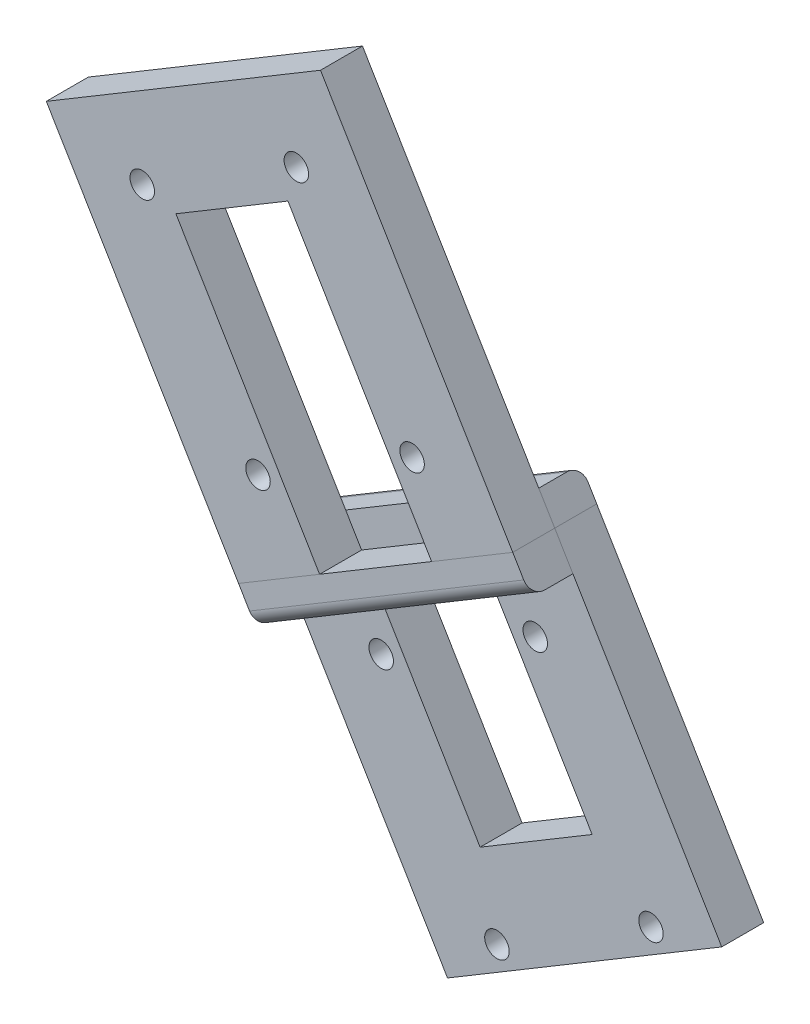
SolidWorks part; units mm, degrees
ref_plane "前视基准面" through (0, 0, 0) normal (0, 0, 1) x (1, 0, 0)
ref_plane "上视基准面" through (0, 0, 0) normal (0, 1, 0) x (1, 0, 0)
ref_plane "右视基准面" through (0, 0, 0) normal (1, 0, 0) x (0, 0, -1)
other "Configuration Table"
sketch "草图2" plane through (0, 0, 0) normal (0, 0, 1) x (1, 0, 0)
  line L2 (-562.0337, 913.0338) -> (-46.9087, 51.8379) construction
  line L5 (-22.0945, -34.1131) -> (-73.4273, 51.7061)
  line L6 (-34.2499, 75.1409) -> (-73.4273, 51.7061)
  line L7 (-34.2499, 75.1409) -> (17.083, -10.6784)
  line L8 (17.083, -10.6784) -> (-22.0945, -34.1131)
  line L9 (-6.7787, 29.214) -> (-18.3643, 22.284)
  line L14 (-6.7787, 29.214) -> (-18.3643, 22.284) construction
  line L15 (-34.2499, 75.1409) -> (17.083, -10.6784)
  line L16 (17.083, -10.6784) -> (-22.0945, -34.1131)
  line L17 (-22.0945, -34.1131) -> (-73.4273, 51.7061)
  line L18 (-34.2499, 75.1409) -> (-73.4273, 51.7061)
  line L19 (-38.9054, 56.6252) -> (-1.4325, -6.0229)
  line L20 (-1.4325, -6.0229) -> (-17.4389, -15.5974)
  line L21 (-17.4389, -15.5974) -> (-54.9119, 47.0506)
  line L22 (-38.9054, 56.6252) -> (-54.9119, 47.0506)
  line L23 (-9.4357, -10.8101) -> (526.6252, -907.007) construction
  line L24 (-34.3708, 12.7097) -> (-45.9564, 5.7798)
  line L25 (-34.3708, 12.7097) -> (-45.9564, 5.7798) construction
  circle A0 centre (-43.1752, 20.6108) radius 1.75 construction
  circle A1 centre (-21.1611, 33.7781) radius 1.75 construction
  circle A2 centre (-59.7122, 48.2576) radius 1.75 construction
  circle A3 centre (-37.6984, 61.4255) radius 1.75 construction
  circle A4 centre (-43.1752, 20.6108) radius 1.75
  circle A5 centre (-21.1611, 33.7781) radius 1.75
  circle A6 centre (-59.7122, 48.2576) radius 1.75
  circle A7 centre (-37.6984, 61.4255) radius 1.75
  circle A8 centre (6.9773, -13.2642) radius 1.75
  circle A9 centre (-15.0368, -26.4315) radius 1.75
  circle A10 centre (-31.5738, 1.2153) radius 1.75
  circle A11 centre (-9.56, 14.3832) radius 1.75
  point P36 (0, 0)
  circle M17 centre (-37.6984, 61.4255) radius 1.75
  circle M18 centre (-59.7122, 48.2576) radius 1.75
  circle M19 centre (-43.1752, 20.6108) radius 1.75
  circle M24 centre (-21.1611, 33.7781) radius 1.75
  arc M29 (-26.0215, 33.3432) -> (-24.3219, 32.2889) centre (-24.2586, 34.2879) ccw
  arc M30 (-24.3219, 32.2889) -> (-23.0277, 31.7586) centre (-24.3852, 30.2899) cw
  arc M31 (-23.0277, 31.7586) -> (-19.5648, 36.0174) centre (-21.1611, 33.7781) ccw
  arc M32 (-19.5648, 36.0174) -> (-20.1027, 38.7014) centre (-18.4039, 37.646) cw
  arc M33 (-20.1027, 38.7014) -> (-15.0628, 52.7838) centre (-50.2567, 57.4361) ccw
  arc M61 (-62.7646, 24.2125) -> (-48.0136, 22.007) centre (-50.2567, 57.4361) ccw
  arc M62 (-48.0136, 22.007) -> (-45.9032, 20.2635) centre (-47.8872, 20.011) cw
  arc M63 (-45.9032, 20.2635) -> (-40.513, 21.3001) centre (-43.1752, 20.6108) ccw
  arc M64 (-40.513, 21.3001) -> (-40.368, 22.6912) centre (-38.5769, 21.8014) cw
  arc M65 (-40.368, 22.6912) -> (-40.493, 24.6873) centre (-42.1592, 23.581) ccw
  dimension "D1" = 13.5
extrude "凸台-拉伸1" add sketch "草图2" along normal blind 6 contours L22 L19 L7 L6 L5 L21 M29 M30 M31 M32 M33 M61 M62 M63 M64 M65 M18 M24 M19 M17 | L19 L9 L7 M29 M33 M32 M31 M30 | L24 L21 L17 M65 M64 M63 M62 M61
sketch "草图3" plane through (0, 0, 0) normal (0, 0, -1) x (-1, 0, 0)
  line L0 (34.3708, 12.7097) -> (45.9564, 5.7798) construction
  line L1 (6.7787, 29.214) -> (18.3643, 22.284) construction
  line L2 (34.3708, 12.7097) -> (45.9564, 5.7798)
  line L3 (6.7787, 29.214) -> (18.3643, 22.284)
  line L4 (38.9054, 56.6252) -> (1.4325, -6.0229)
  line L5 (1.4325, -6.0229) -> (17.4389, -15.5974)
  line L6 (17.4389, -15.5974) -> (54.9119, 47.0506)
  line L7 (54.9119, 47.0506) -> (38.9054, 56.6252)
  line L8 (38.9054, 56.6252) -> (1.4325, -6.0229)
  line L9 (1.4325, -6.0229) -> (17.4389, -15.5974)
  line L10 (17.4389, -15.5974) -> (54.9119, 47.0506)
  line L11 (54.9119, 47.0506) -> (38.9054, 56.6252)
  line L12 (34.2499, 75.1409) -> (-17.083, -10.6784)
  line L13 (-17.083, -10.6784) -> (22.0945, -34.1131)
  line L14 (22.0945, -34.1131) -> (73.4273, 51.7061)
  line L15 (73.4273, 51.7061) -> (34.2499, 75.1409)
  line L16 (34.2499, 75.1409) -> (-17.083, -10.6784)
  line L17 (-17.083, -10.6784) -> (22.0945, -34.1131)
  line L18 (22.0945, -34.1131) -> (73.4273, 51.7061)
  line L19 (73.4273, 51.7061) -> (34.2499, 75.1409)
  line L20 (34.2499, 75.1409) -> (-17.083, -10.6784)
  line L21 (-17.083, -10.6784) -> (22.0945, -34.1131)
  line L22 (22.0945, -34.1131) -> (73.4273, 51.7061)
  line L23 (73.4273, 51.7061) -> (34.2499, 75.1409)
  line L24 (34.2499, 75.1409) -> (-17.083, -10.6784)
  line L25 (-17.083, -10.6784) -> (22.0945, -34.1131)
  line L26 (22.0945, -34.1131) -> (73.4273, 51.7061)
  line L27 (73.4273, 51.7061) -> (34.2499, 75.1409)
  circle A1 centre (37.6984, 61.4255) radius 1.75
  circle A2 centre (37.6984, 61.4255) radius 1.75
  circle A3 centre (59.7122, 48.2576) radius 1.75
  circle A4 centre (59.7122, 48.2576) radius 1.75
  circle A5 centre (21.1611, 33.7781) radius 1.75
  circle A6 centre (21.1611, 33.7781) radius 1.75
  circle A7 centre (43.1752, 20.6108) radius 1.75
  circle A8 centre (43.1752, 20.6108) radius 1.75
  circle A9 centre (9.56, 14.3832) radius 1.75
  circle A10 centre (9.56, 14.3832) radius 1.75
  circle A11 centre (31.5738, 1.2153) radius 1.75
  circle A12 centre (31.5738, 1.2153) radius 1.75
  circle A13 centre (15.0368, -26.4315) radius 1.75
  circle A14 centre (15.0368, -26.4315) radius 1.75
  circle A15 centre (-6.9773, -13.2642) radius 1.75
  circle A16 centre (-6.9773, -13.2642) radius 1.75
  line M23 (34.3708, 12.7097) -> (45.9564, 5.7798)
  line M27 (6.7787, 29.214) -> (18.3643, 22.284)
  dimension "D1" = 0
  dimension "D2" = 0
  dimension "D3" = 0
  dimension "D4" = 0
  dimension "D5" = 0
  dimension "D6" = 0
  dimension "D7" = 0
  dimension "D8" = 0
  dimension "D9" = 0
  dimension "D10" = 0
  dimension "D11" = 0
extrude "凸台-拉伸2" add sketch "草图3" along normal blind 6 separate body contours L17 L18 L10 L9 L8 L16 A16 A14 A12 A10 M23 M27
sketch "草图4" plane through (7.8773, 4.7118, 0) normal (0.8582, 0.5133, 0) x (0, 0, -1)
  line L0 (0, 28.5509) -> (0, -17.9333) construction
  line L1 (0, -17.9333) -> (6, -17.9333) construction
  line L2 (6, -17.9333) -> (6, 28.5509) construction
  line L3 (6, 28.5509) -> (0, 28.5509) construction
  line L4 (0, 28.5509) -> (0, 82.0667) construction
  line L5 (0, 82.0667) -> (-6, 82.0667) construction
  line L6 (-6, 82.0667) -> (-6, 28.5509) construction
  line L7 (-6, 28.5509) -> (0, 28.5509) construction
  line L8 (0, 28.5509) -> (0, -17.9333)
  line L9 (0, -17.9333) -> (6, -17.9333)
  line L10 (6, -17.9333) -> (6, 28.5509)
  line L11 (6, 28.5509) -> (0, 28.5509)
  line L12 (0, 28.5509) -> (0, 82.0667)
  line L13 (0, 82.0667) -> (-6, 82.0667)
  line L14 (-6, 82.0667) -> (-6, 28.5509)
  line L15 (-6, 28.5509) -> (0, 28.5509)
  line L16 (-6, 28.5509) -> (-6, 25.4904)
  line L17 (-4, 23.4904) -> (0, 23.4904)
  line L18 (0, 23.4904) -> (6, 23.4904)
  line L19 (6, 23.4904) -> (6, 30.9923)
  line L20 (4, 32.9923) -> (-6, 32.9923)
  line L21 (-6, 32.9923) -> (-6, 23.4904)
  arc A0 (6, 30.9923) -> (4, 32.9923) centre (4, 30.9923) ccw
  arc A1 (-6, 25.4904) -> (-4, 23.4904) centre (-4, 25.4904) ccw
  line M1 (0, 28.5509) -> (0, -17.9333)
  line M4 (6, 28.5509) -> (0, 28.5509)
  dimension "D1" = 2
extrude "凸台-拉伸17" add sketch "草图4" against normal up to surface (45.6515 mm away) separate body contours L16 A1 L17 L15 M1 | L19 A0 L20 L12 M4 up to face at (-59.6919, 28.7429, 3)
